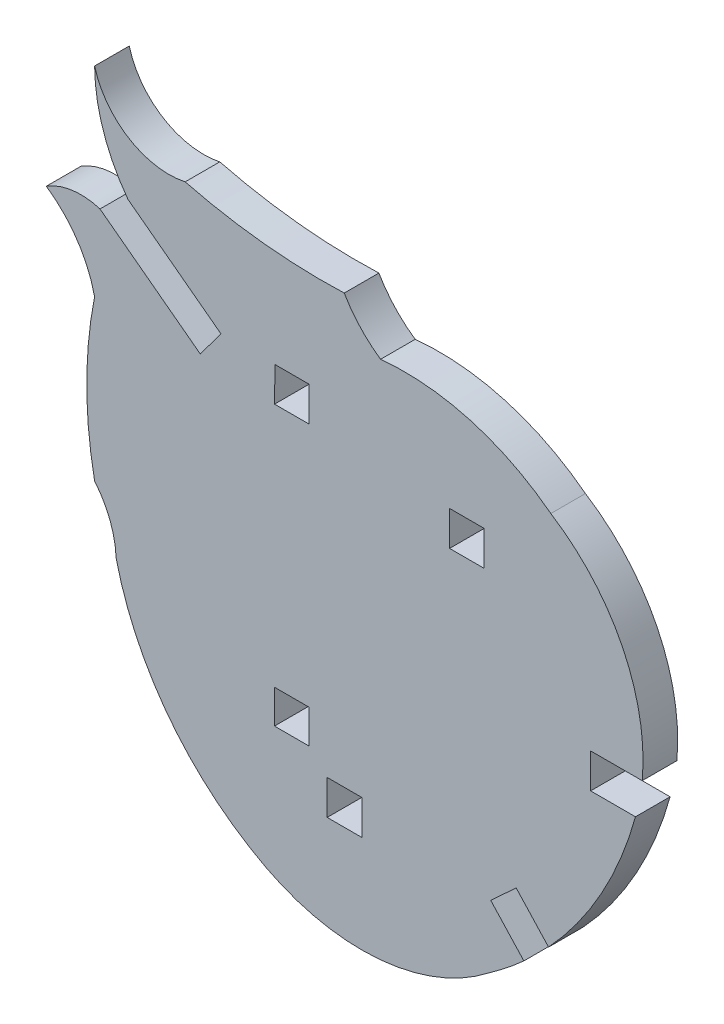
SolidWorks part; units mm, degrees
ref_plane "Front Plane" through (0, 0, 0) normal (0, 0, 1) x (1, 0, 0)
ref_plane "Top Plane" through (0, 0, 0) normal (0, 1, 0) x (1, 0, 0)
ref_plane "Right Plane" through (0, 0, 0) normal (1, 0, 0) x (0, 0, -1)
sketch "Sketch1" plane through (0, 0, 0) normal (0, 0, 1) x (1, 0, 0)
  line L0 (-1.5026, 64.2052) -> (0, 64.2052)
  line L2 (0, 64.2052) -> (0, 62.6848)
  line L3 (0, 62.6848) -> (-1.5197, 62.6848)
  line L4 (-1.5197, 62.6848) -> (-1.5026, 64.2052)
  line L5 (0, 51.8949) -> (0, 50.4131)
  line L6 (0, 50.4131) -> (-1.524, 50.4131)
  line L7 (-1.524, 50.4131) -> (-1.524, 51.8949)
  line L10 (-1.524, 51.8949) -> (0, 51.8949)
  line L11 (-10.4937, 68.209) -> (-4.333, 63.5736) construction
  line L12 (7.7078, 62.5622) -> (6.1838, 62.5622)
  line L13 (7.7078, 62.5622) -> (7.7078, 61.0382)
  line L14 (7.7078, 61.0382) -> (6.1838, 61.0382)
  line L15 (6.1838, 62.5622) -> (6.1838, 61.0382)
  line L16 (2.3202, 49.6157) -> (0.7962, 49.6157)
  line L17 (2.3202, 49.6157) -> (2.3202, 48.0917)
  line L18 (2.3202, 48.0917) -> (0.7962, 48.0917)
  line L19 (0.7962, 49.6157) -> (0.7962, 48.0917)
  line L20 (-9.2019, 66.2834) -> (-4.7912, 62.9647)
  line L21 (-7.9672, 67.2617) -> (-3.8749, 64.1825)
  line L23 (-4.7912, 62.9647) -> (-3.8749, 64.1825)
  line L25 (-10.9518, 67.6001) -> (-4.7912, 62.9647) construction
  line L26 (-10.0356, 68.8179) -> (-3.8749, 64.1825) construction
  arc A0 (-11.5637, 65.9693) -> (-9.4398, 62.8184) centre (-14.5138, 61.6895) cw
  arc A1 (-9.4398, 62.8184) -> (-9.4398, 55.7982) centre (8.2402, 59.3083) ccw
  arc A2 (-9.4398, 55.7982) -> (-8.4904, 53.3231) centre (-12.6048, 53.1645) cw
  arc A3 (-8.4904, 53.3231) -> (-1.8901, 44.8334) centre (4.1044, 56.3044) ccw
  arc A4 (-1.8901, 44.8334) -> (7.9175, 45.7272) centre (2.3202, 52.8901) ccw
  arc A5 (7.9175, 45.7272) -> (14.5828, 55.7982) centre (-1.6249, 59.2839) ccw
  arc A6 (14.5828, 55.7982) -> (10.6387, 64.5949) centre (5.951, 57.2106) ccw
  arc A7 (10.6387, 64.5949) -> (3.1452, 66.7269) centre (4.2068, 56.2236) ccw
  arc A8 (3.1452, 66.7269) -> (1.5476, 68.4536) centre (6.1838, 71.1407) cw
  arc A9 (1.5476, 68.4536) -> (-5.4544, 69.1901) centre (0.5901, 93.0056) cw
  arc A10 (-5.4544, 69.1901) -> (-9.4398, 71.6133) centre (-6.1667, 72.5076) cw
  arc A11 (-9.4398, 71.6133) -> (-7.9672, 67.2617) centre (-2.1152, 71.6669) ccw
  arc A12 (-11.5637, 65.9693) -> (-9.2019, 66.2834) centre (-10.0418, 63.5631) cw
  spline S0 degree 3 poles (4.8728, 61.0507) (7.3839, 59.5742) (9.7906, 59.2356) (12.9129, 59.4581) (11.0648, 64.1249) (7.6878, 65.1499) (4.7299, 65.4543) (1.0285, 65.8681) (1.9625, 61.8446) (4.8728, 61.0507) (7.3839, 59.5742) (9.7906, 59.2356) knots -0.336718 -0.22814 -0.130925 0 0.094465 0.158663 0.295652 0.457811 0.557025 0.663282 0.77186 0.869075 1 1.094465 1.158663 1.295652 only from (7.7078, 59.6665) to (7.7078, 59.6665) construction
  spline S1 degree 3 poles (-5.0229, 48.1086) (-7.9104, 52.3314) (-10.0434, 56.0697) (-10.1225, 60.1668) (-8.4867, 62.1372) (-5.5291, 62.0137) (-4.195, 58.5953) (-2.7053, 55.8265) (-0.6971, 53.5004) (-0.2643, 49.6486) (-5.0229, 48.1086) (-7.9104, 52.3314) (-10.0434, 56.0697) knots -0.322789 -0.217256 -0.10736 0 0.187161 0.282081 0.339122 0.39125 0.510585 0.617524 0.677211 0.782744 0.89264 1 1.187161 1.282081 1.339122 only from (-7.2756, 51.4652) to (-7.2756, 51.4652) construction
  dimension "D1" = 1.524
  dimension "D2" = 1.524
  dimension "D3" = 1.524
  dimension "D4" = 1.524
  dimension "D5" = 0.762
  dimension "D6" = 0.762
extrude "Boss-Extrude1" add sketch "Sketch1" along normal blind 1.524
sketch "Sketch2" plane through (0, 0, 1.524) normal (0, 0, 1) x (1, 0, 0)
  line L0 (10.279, 47.1781) -> (8.5538, 49.0471) construction
  line L1 (10.8389, 47.695) -> (9.1137, 49.5639)
  line L2 (9.7191, 46.6613) -> (7.9939, 48.5302)
  line L3 (10.8389, 47.695) -> (9.7191, 46.6613)
  line L4 (9.1137, 49.5639) -> (7.9939, 48.5302)
  line L5 (15.2917, 55.6623) -> (12.3905, 55.6623) construction
  line L6 (15.2917, 56.4243) -> (12.3905, 56.4243)
  line L7 (15.2917, 54.9003) -> (12.3905, 54.9003)
  line L8 (15.2917, 56.4243) -> (15.2917, 54.9003)
  line L9 (12.3905, 56.4243) -> (12.3905, 54.9003)
  dimension "D1" = 0.762
  dimension "D2" = 0.762
  dimension "D3" = 0.762
  dimension "D4" = 0.762
extrude "Cut-Extrude1" cut sketch "Sketch2" against normal blind 1.524
